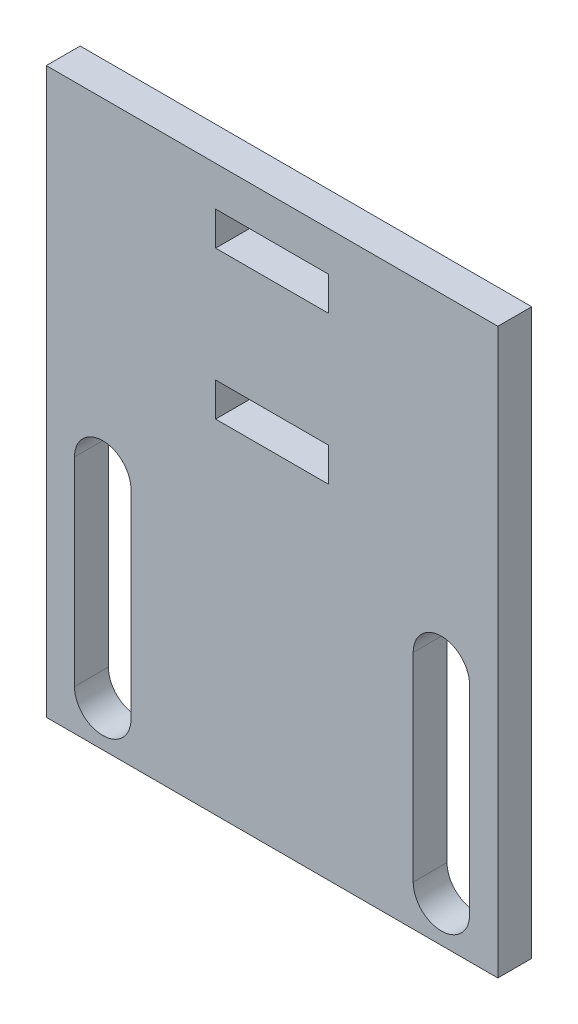
SolidWorks part; units mm, degrees
ref_plane "Front Plane" through (0, 0, 0) normal (0, 0, 1) x (1, 0, 0)
ref_plane "Top Plane" through (0, 0, 0) normal (0, 1, 0) x (1, 0, 0)
ref_plane "Right Plane" through (0, 0, 0) normal (1, 0, 0) x (0, 0, -1)
sketch "Sketch1" plane through (0, 0, 0) normal (0, 0, 1) x (1, 0, 0)
  line L5 (0, 0) -> (0, 25) construction
  line L6 (20, -25) -> (-20, -25)
  line L8 (20, -25) -> (20, 25)
  line L9 (20, 25) -> (-20, 25)
  line L10 (-20, -25) -> (-20, 25)
  line L11 (20, -25) -> (-20, 25) construction
  line L16 (20, 25) -> (-20, -25) construction
  line L17 (0, 0) -> (0, -25) construction
  line L18 (5, 18.4922) -> (-5, 18.4922)
  line L19 (5, 18.4922) -> (5, 21.4922)
  line L20 (5, 21.4922) -> (-5, 21.4922)
  line L21 (-5, 18.4922) -> (-5, 21.4922)
  line L22 (5, 18.4922) -> (-5, 21.4922) construction
  line L23 (5, 21.4922) -> (-5, 18.4922) construction
  line L24 (5, 5.3781) -> (-5, 5.3781)
  line L25 (5, 5.3781) -> (5, 8.3781)
  line L26 (5, 8.3781) -> (-5, 8.3781)
  line L27 (-5, 5.3781) -> (-5, 8.3781)
  line L28 (5, 5.3781) -> (-5, 8.3781) construction
  line L29 (5, 8.3781) -> (-5, 5.3781) construction
  line L30 (-12.5, -3.7753) -> (-12.5, -21.3942)
  line L31 (-17.5, -3.7753) -> (-17.5, -21.3942)
  line L32 (12.5, -3.7753) -> (12.5, -21.3942)
  line L33 (17.5, -3.7753) -> (17.5, -21.3942)
  arc A0 (-12.5, -3.7753) -> (-17.5, -3.7753) centre (-15, -3.7753) ccw
  arc A1 (-17.5, -21.3942) -> (-12.5, -21.3942) centre (-15, -21.3942) ccw
  arc A2 (12.5, -3.7753) -> (17.5, -3.7753) centre (15, -3.7753) cw
  arc A3 (17.5, -21.3942) -> (12.5, -21.3942) centre (15, -21.3942) cw
  point P0 (0, 0)
  point P7 (0, 19.9922)
  point P12 (0, 6.8781)
  dimension "D3" = 10
  dimension "D4" = 3
  dimension "D5" = 10
  dimension "D7" = 5
  dimension "D8" = 5
  dimension "D1" = 50
  dimension "D2" = 40
  dimension "D6" = 3
  dimension "D9" = 30
extrude "Boss-Extrude1" add sketch "Sketch1" along normal blind 3
